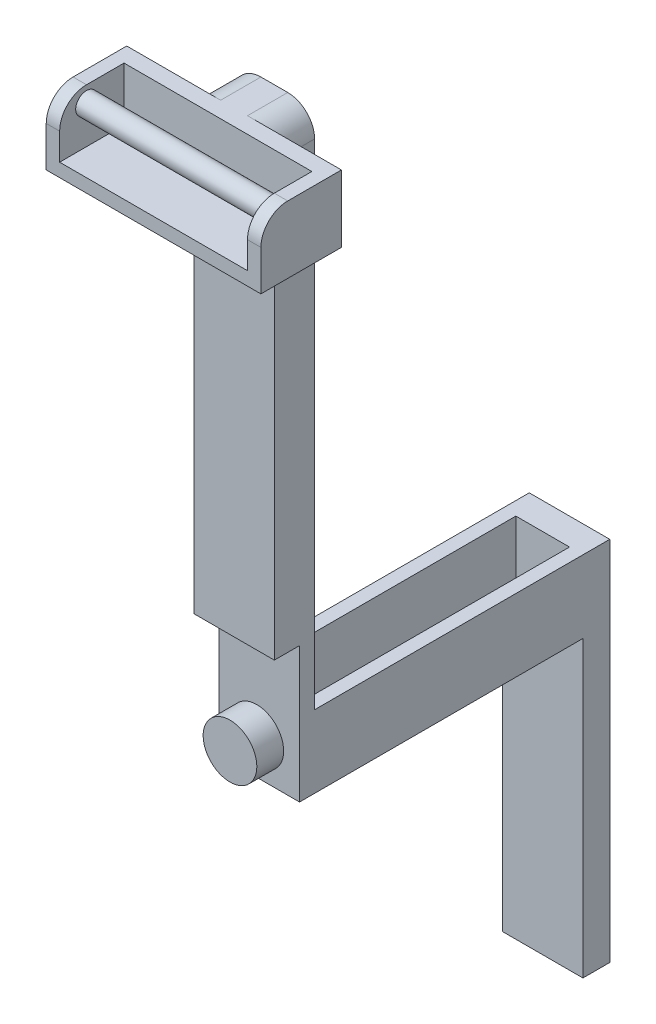
SolidWorks part; units mm, degrees
ref_plane "Front Plane" through (0, 0, 0) normal (0, 0, 1) x (1, 0, 0)
ref_plane "Top Plane" through (0, 0, 0) normal (0, 1, 0) x (1, 0, 0)
ref_plane "Right Plane" through (0, 0, 0) normal (1, 0, 0) x (0, 0, -1)
sketch "Sketch1" plane through (0, 0, 0) normal (0, 0, 1) x (1, 0, 0)
  line L0 (50, 212.065) -> (-20, 212.065) construction
  line L1 (30, -62.835) -> (0, -62.835)
  line L2 (30, -62.835) -> (30, 419.765)
  line L3 (30, 419.765) -> (0, 419.765)
  line L4 (0, -62.835) -> (0, 419.765)
  line L5 (30, -62.835) -> (0, 419.765) construction
  line L6 (30, 419.765) -> (0, -62.835) construction
  line L7 (50, 198.565) -> (-20, 198.565)
  line L8 (50, 225.565) -> (-20, 225.565)
  arc A0 (50, 198.565) -> (50, 225.565) centre (50, 212.065) ccw
  arc A1 (-20, 225.565) -> (-20, 198.565) centre (-20, 212.065) ccw
  point P0 (15, 178.465)
  point P7 (15, 212.065)
  dimension "D1" = 482.6
  dimension "D2" = 27
  dimension "D3" = 30
  dimension "D4" = 33.6
  dimension "D5" = 70
  dimension "D6" = 0
extrude "Extrude1" add sketch "Sketch1" along normal blind 15 contours L8 L2 L3 L4 | L7 A0 L8 L2 | L2 L8 L4 L7 | L8 A1 L7 L4 | L2 L7 L4 L1
fillet "Fillet1" radius 10 4 edges at (30, -62.835, 7.5) (0, -62.835, 7.5) (0, 419.765, 7.5) (30, 419.765, 7.5)
sketch "Sketch2" plane through (0, 0, 0) normal (0, 0, -1) x (-1, 0, 0)
  line L0 (-50, 225.565) -> (-30, 225.565) construction
  line L1 (-50, 198.565) -> (-30, 198.565) construction
  line L2 (0, 198.565) -> (20, 198.565) construction
  line L3 (0, 225.565) -> (20, 225.565) construction
  line L4 (-50, 225.565) -> (-30, 225.565)
  line L5 (-50, 198.565) -> (-30, 198.565)
  line L6 (0, 198.565) -> (20, 198.565)
  line L7 (0, 225.565) -> (20, 225.565)
  line L8 (-30, 225.565) -> (-30, 198.565)
  line L9 (0, 225.565) -> (0, 198.565)
  arc A0 (20, 198.565) -> (20, 225.565) centre (20, 212.065) ccw construction
  arc A1 (-50, 225.565) -> (-50, 198.565) centre (-50, 212.065) ccw construction
  arc A2 (20, 198.565) -> (20, 225.565) centre (20, 212.065) ccw
  arc A3 (-50, 225.565) -> (-50, 198.565) centre (-50, 212.065) ccw
extrude "Extrude2" cut sketch "Sketch2" against normal blind 10
sketch "Sketch3" plane through (0, 0, 15) normal (0, 0, 1) x (1, 0, 0)
  line L0 (30, 407.265) -> (0, 407.265) construction
  line L1 (-25, 394.765) -> (55, 394.765)
  line L2 (-25, 394.765) -> (-25, 419.765)
  line L3 (-25, 419.765) -> (55, 419.765)
  line L4 (55, 394.765) -> (55, 419.765)
  line L5 (-25, 394.765) -> (55, 419.765) construction
  line L6 (-25, 419.765) -> (55, 394.765) construction
  line L7 (30, 225.565) -> (30, 409.765) construction
  line L8 (0, 225.565) -> (0, 409.765) construction
  line L9 (15, 407.265) -> (15, 419.765) construction
  line L10 (20, 419.765) -> (10, 419.765) construction
  point P0 (15, 407.265)
  dimension "D1" = 80
  dimension "D2" = 0
  dimension "D3" = 25
  dimension "D4" = 0
extrude "Extrude3" add sketch "Sketch3" along normal blind 30
sketch "Sketch5" plane through (0, 0, 45) normal (0, 0, 1) x (1, 0, 0)
  line L0 (55, 419.765) -> (-25, 419.765) construction
  line L1 (-20, 419.765) -> (50, 419.765)
  line L2 (-20, 419.765) -> (-20, 399.765)
  line L3 (-20, 399.765) -> (50, 399.765)
  line L4 (50, 419.765) -> (50, 399.765)
  line L5 (-25, 419.765) -> (-25, 394.765) construction
  line L6 (55, 394.765) -> (55, 419.765) construction
  line L7 (-25, 394.765) -> (55, 394.765) construction
  dimension "D1" = 5
  dimension "D2" = 5
  dimension "D3" = 5
extrude "Extrude4" cut sketch "Sketch5" against normal blind 24
fillet "Fillet2" radius 10 2 edges at (-22.5, 419.765, 45) (52.5, 419.765, 45)
sketch "Sketch6" plane through (50, 0, 0) normal (-1, 0, 0) x (0, 0, 1)
  circle A0 centre (35, 413.8477) radius 4.0292
extrude "Extrude5" add sketch "Sketch6" along normal up to next
sketch "Sketch7" plane through (0, 0, 0) normal (0, 0, -1) x (-1, 0, 0)
  line L0 (0, 198.565) -> (-30, 198.565)
  line L1 (-30, 198.565) -> (-30, -64.8073)
  line L2 (-30, -64.8073) -> (0, -64.8073)
  line L3 (0, -64.8073) -> (0, 198.565)
extrude "Extrude6" cut sketch "Sketch7" against normal through all
sketch "Sketch8" plane through (0, 0, 0) normal (0, 0, -1) x (-1, 0, 0)
  line L0 (-30, 198.565) -> (0, 198.565)
  line L1 (0, 198.565) -> (0, 225.565)
  line L2 (0, 225.565) -> (-5, 225.565)
  line L3 (-5, 225.565) -> (-5, 203.565)
  line L4 (-5, 203.565) -> (-25, 203.565)
  line L5 (-25, 203.565) -> (-25, 225.565)
  line L6 (-25, 225.565) -> (-30, 225.565)
  line L7 (-30, 198.565) -> (-30, 225.565) construction
  line L8 (-30, 198.565) -> (-30, 409.765) construction
  line L9 (-30, 225.565) -> (-30, 198.565)
  dimension "D1" = 5
  dimension "D2" = 5
  dimension "D3" = 5
extrude "Extrude7" add sketch "Sketch8" along normal blind 100
sketch "Sketch9" plane through (0, 0, -100) normal (0, 0, -1) x (-1, 0, 0)
  line L1 (-30, 225.565) -> (0, 225.565)
  line L2 (-30, 225.565) -> (-30, 88.9838)
  line L3 (-30, 88.9838) -> (0, 88.9838)
  line L4 (0, 225.565) -> (0, 88.9838)
extrude "Extrude8" add sketch "Sketch9" along normal blind 10
hole_wizard "1/4 (0.25) Diameter Hole1" positions "3DSketch1" profile "Sketch10" hole size "1/4" standard "Ansi Inch"
sketch3d "3DSketch1"
  line L0 (-20, 212.065, 15) -> (-20, 212.065, 10) construction
  line L1 (50, 212.065, 15) -> (50, 212.065, 10) construction
  point P0 (-20, 212.065, 10)
  point P4 (50, 212.065, 10)
sketch "Sketch10" plane through (-20, 212.065, 10) normal (1, 0, 0) x (0, 1, 0)
  line L0 (0, 0) -> (0, 11.9077)
  line L1 (0, 11.9077) -> (3.175, 10)
  line L2 (3.175, 10) -> (3.175, 0)
  line L5 (3.175, 0) -> (0, 0)
  line L10 (0, 11.9077) -> (-3.175, 10) construction
  line L11 (0, -6.35) -> (0, 107.95) construction
  dimension "Hole Dia." = 6.35
  dimension "Hole Depth" = 10
  dimension "Drill Angle" = 118
sketch "Sketch11" plane through (30, 0, 0) normal (1, 0, 0) x (0, 0, -1)
  line L0 (-15, 225.565) -> (-15, 394.765) construction
  line L1 (-15, 249.065) -> (-5.6029, 249.065)
  line L2 (-15, 249.065) -> (-15, 198.565)
  line L3 (-15, 198.565) -> (-5.6029, 198.565)
  line L4 (-5.6029, 249.065) -> (-5.6029, 198.565)
  line L5 (-10, 198.565) -> (100, 198.565) construction
  line L6 (-10, 198.565) -> (-10, 225.565) construction
  point P8 (-10, 212.065)
  dimension "D1" = 50.5
extrude "Extrude10" cut sketch "Sketch11" against normal through all and the other way through all
sketch "Sketch12" plane through (0, 0, 5.6029) normal (0, 0, 1) x (1, 0, 0)
  circle A0 centre (14.0801, 212.0606) radius 10
extrude "Extrude11" add sketch "Sketch12" along normal blind 10
